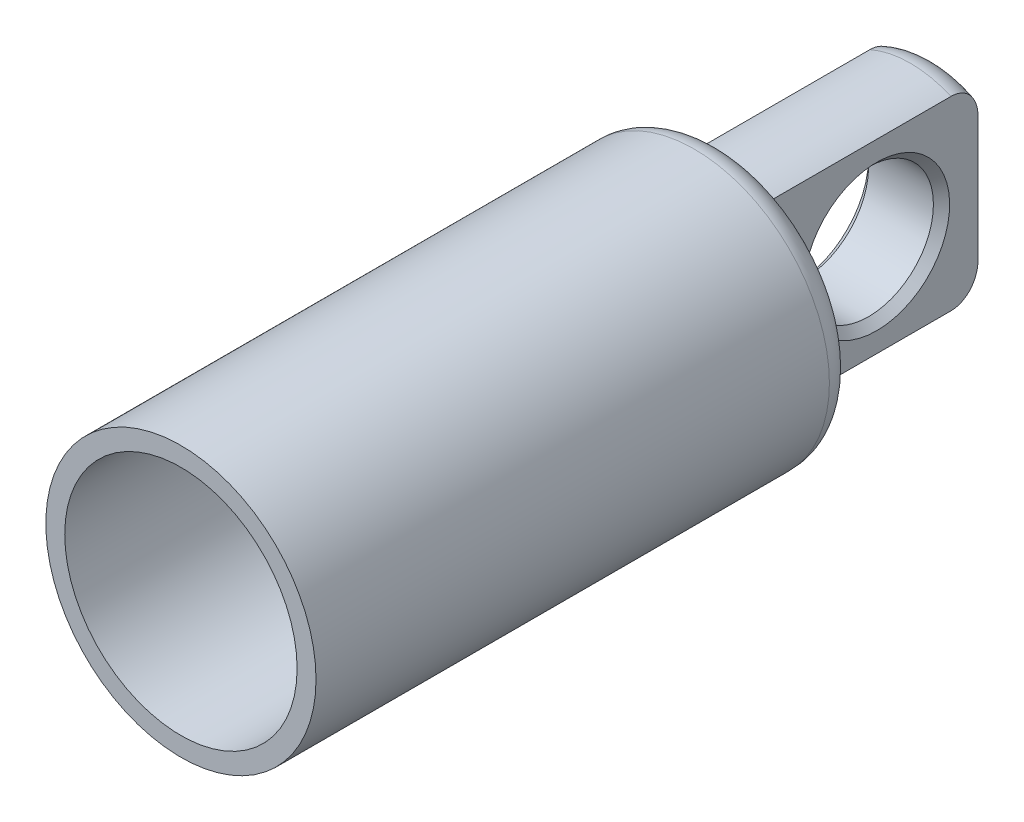
SolidWorks part; units mm, degrees
ref_plane "Front Plane" through (0, 0, 0) normal (0, 0, 1) x (1, 0, 0)
ref_plane "Top Plane" through (0, 0, 0) normal (0, 1, 0) x (1, 0, 0)
ref_plane "Right Plane" through (0, 0, 0) normal (1, 0, 0) x (0, 0, -1)
sketch "Sketch1" plane through (0, 0, 0) normal (0, 0, 1) x (1, 0, 0)
  circle A0 centre (0, 0) radius 6.35
  dimension "D1" = 12.7
extrude "Boss-Extrude1" add sketch "Sketch1" along normal blind 25.4
cosmetic thread "Cosmetic Thread1" parameters "D1"=19.05, "D2"=11.1887
shell "Shell1" thickness 0.889
cosmetic thread "Cosmetic Thread2" parameters "D1"=9.525, "D2"=12.7
fillet "Fillet1" radius 1.27 1 edges at (6.35, 0, 0)
sketch "Sketch2" plane through (0, 0, 0) normal (0, 0, -1) x (-1, 0, 0)
  circle A0 centre (0, 0) radius 4.7625
  dimension "D1" = 9.525
extrude "Boss-Extrude2" add sketch "Sketch2" along normal blind 10.16
sketch "Sketch3" plane through (0, 0, -10.16) normal (0, 0, -1) x (-1, 0, 0)
  line L0 (0, -1000) -> (0, 49000) construction
  line L1 (-1.905, 4.3649) -> (-1.905, -4.3649)
  line L2 (1.905, 4.3649) -> (1.905, -4.3649)
  circle A0 centre (0, 0) radius 4.7625 construction
  circle A1 centre (0, 0) radius 4.7625 construction
  arc A2 (-1.905, 4.3649) -> (-1.905, -4.3649) centre (0, 0) ccw
  arc A3 (1.905, 4.3649) -> (1.905, -4.3649) centre (0, 0) cw
  dimension "D1" = 3.81
extrude "Cut-Extrude1" cut sketch "Sketch3" against normal blind 10.16
sketch "Sketch4" plane through (1.905, 0, 0) normal (1, 0, 0) x (0, 0, -1)
  line L0 (10.16, -4.3649) -> (10.16, 4.3649) construction
  circle A0 centre (5.3975, 0) radius 3.048
  dimension "D1" = 6.096
  dimension "D2" = 4.7625
extrude "Cut-Extrude2" cut sketch "Sketch4" against normal through all both and the other way through all contours A0
chamfer "Chamfer2" distance 0.381 angle 45 2 edges at (-1.905, 3.048, -5.3975) (1.905, -3.048, -5.3975)
fillet "Fillet2" radius 1.27 2 edges at (0, -4.7625, -10.16) (0, 4.7625, -10.16)
